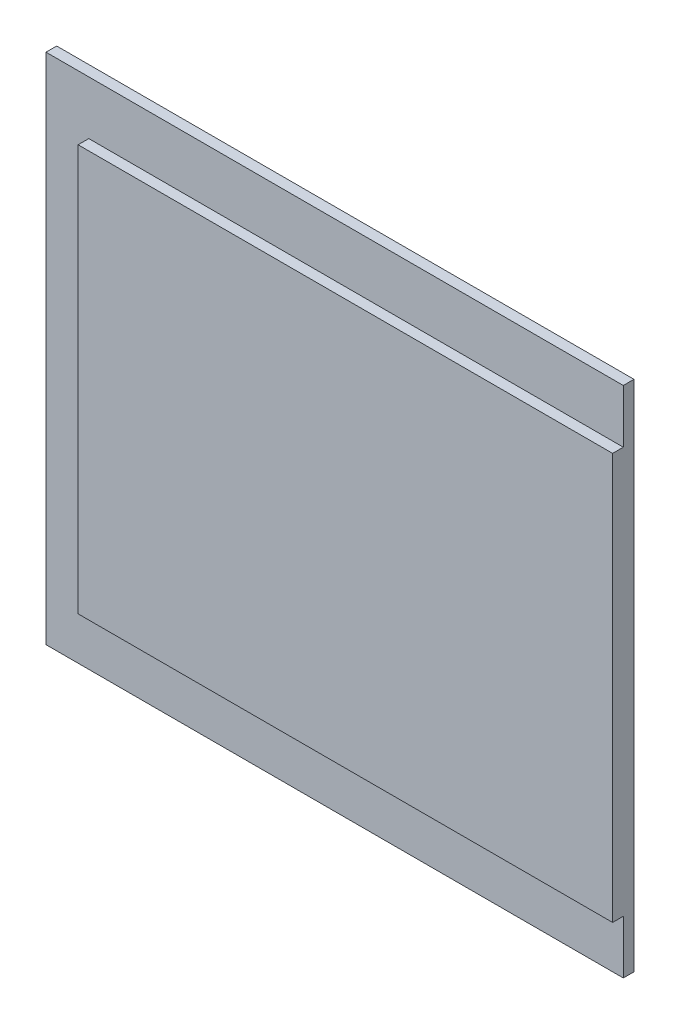
SolidWorks part; units mm, degrees
material "Акрил (Средняя-высокая ударопрочность)"
ref_plane "Спереди" through (0, 0, 0) normal (0, 0, 1) x (1, 0, 0)
ref_plane "Сверху" through (0, 0, 0) normal (0, 1, 0) x (1, 0, 0)
ref_plane "Справа" through (0, 0, 0) normal (1, 0, 0) x (0, 0, -1)
sketch "Эскиз1" plane through (0, 0, 0) normal (0, 0, 1) x (1, 0, 0)
  line L1 (-27, -24) -> (27, -24)
  line L2 (-27, -24) -> (-27, 24)
  line L3 (-27, 24) -> (27, 24)
  line L4 (27, -24) -> (27, 24)
  line L5 (-27, -24) -> (27, 24) construction
  line L6 (-27, 24) -> (27, -24) construction
  point P0 (0, 0)
  dimension "D1" = 54
  dimension "D2" = 48
extrude "Бобышка-Вытянуть1" add sketch "Эскиз1" along normal blind 1
sketch "Эскиз2" plane through (0, 0, 1) normal (0, 0, 1) x (1, 0, 0)
  line L0 (27, -24) -> (27, 24) construction
  line L1 (-23, -19) -> (27, -19)
  line L2 (-23, -19) -> (-23, 19)
  line L3 (-23, 19) -> (27, 19)
  line L4 (27, -19) -> (27, 19)
  line L5 (-23, -19) -> (27, 19) construction
  line L6 (-23, 19) -> (27, -19) construction
  line L8 (-27, 24) -> (-27, -24) construction
  point P0 (0, 0)
  point P10 (2, 0)
  point P11 (0, 0)
  dimension "D1" = 38
  dimension "D2" = 4
extrude "Бобышка-Вытянуть2" add sketch "Эскиз2" along normal blind 1
